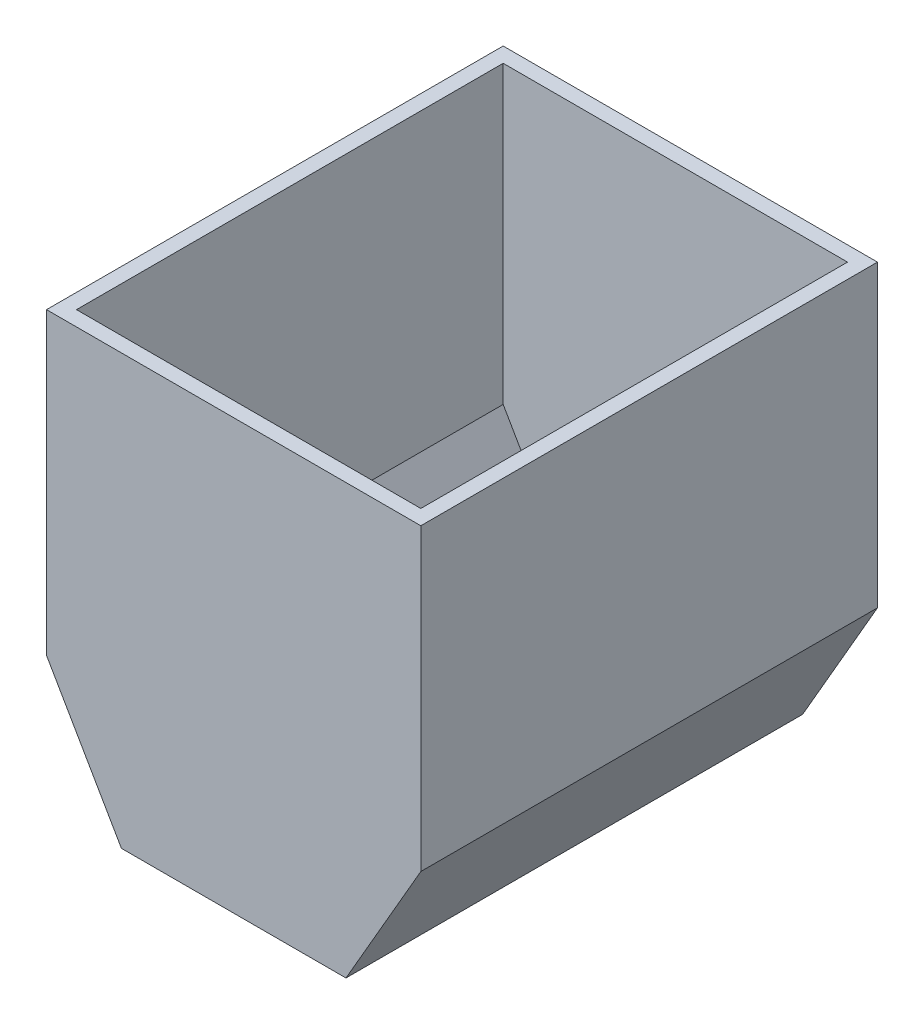
SolidWorks part; units mm, degrees
ref_plane "Front Plane" through (0, 0, 0) normal (0, 0, 1) x (1, 0, 0)
ref_plane "Top Plane" through (0, 0, 0) normal (0, 1, 0) x (1, 0, 0)
ref_plane "Right Plane" through (0, 0, 0) normal (1, 0, 0) x (0, 0, -1)
sketch "Sketch1" plane through (0, 0, 0) normal (0, 0, 1) x (1, 0, 0)
  line L0 (-19.05, 0) -> (19.05, 0)
  line L1 (55, 0) -> (-55, 0) construction
  line L2 (19.05, 0) -> (31.75, 21.997)
  line L3 (31.75, 21.997) -> (31.75, 72.797)
  line L4 (31.75, 72.797) -> (-31.75, 72.797)
  line L5 (-31.75, 72.797) -> (-31.75, 21.997)
  line L6 (-31.75, 21.997) -> (-19.05, 0)
  point P6 (0, 0)
  dimension "D1" = 63.5
  dimension "D2" = 50.8
  dimension "D3" = 150
  dimension "D4" = 25.4
  dimension "D5" = 120
extrude "Boss-Extrude1" add sketch "Sketch1" along normal mid plane 77.47
shell "Shell1" thickness 2.54
sketch "Sketch4" plane through (0, 2.54, 0) normal (0, 1, 0) x (1, 0, 0)
  line L1 (-17.5835, 36.195) -> (17.5835, 36.195)
  line L2 (-17.5835, 36.195) -> (-17.5835, -36.195)
  line L3 (-17.5835, -36.195) -> (17.5835, -36.195)
  line L4 (17.5835, 36.195) -> (17.5835, -36.195)
  line L5 (-17.5835, 36.195) -> (17.5835, -36.195) construction
  line L6 (-17.5835, -36.195) -> (17.5835, 36.195) construction
  point P0 (0, 0)
extrude "Cut-Extrude1" cut sketch "Sketch4" against normal through all
